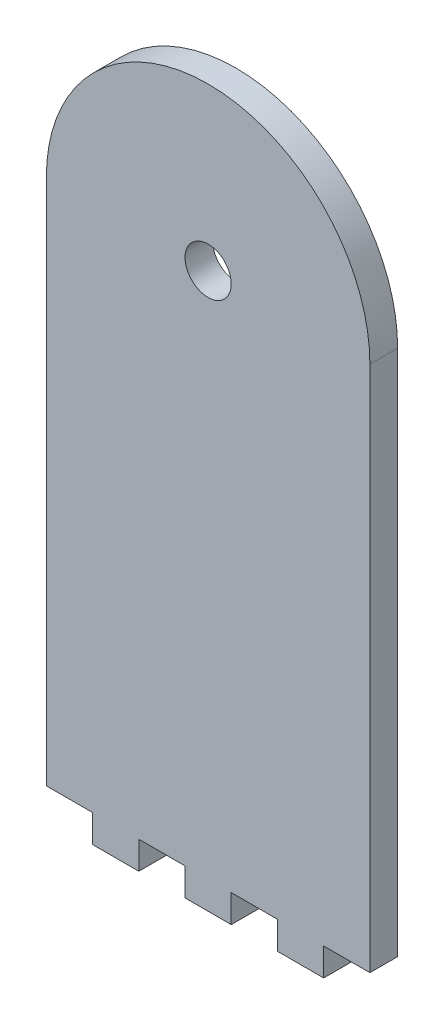
SolidWorks part; units mm, degrees
ref_plane "Alzado" through (0, 0, 0) normal (0, 0, 1) x (1, 0, 0)
ref_plane "Planta" through (0, 0, 0) normal (0, 1, 0) x (1, 0, 0)
ref_plane "Vista lateral" through (0, 0, 0) normal (1, 0, 0) x (0, 0, -1)
sketch "Croquis1" plane through (0, 0, 0) normal (0, 0, 1) x (1, 0, 0)
  line L0 (-17.5, 30) -> (17.5, 30) construction
  line L1 (-12.5, -30) -> (-7.5, -30)
  line L2 (-17.5, -27) -> (-17.5, 30)
  line L4 (17.5, -27) -> (17.5, 30)
  line L5 (-17.5, -30) -> (17.5, 30) construction
  line L6 (-17.5, 30) -> (17.5, -30) construction
  line L22 (-12.5, -30) -> (-12.5, -27)
  line L23 (-17.5, -27) -> (17.5, -27) construction
  line L24 (-17.5, -27) -> (-12.5, -27)
  line L26 (-7.5, -30) -> (-7.5, -27)
  line L27 (-7.5, -27) -> (-2.5, -27)
  line L28 (-2.5, -27) -> (-2.5, -30)
  line L29 (-2.5, -30) -> (2.5, -30)
  line L30 (2.5, -30) -> (2.5, -27)
  line L31 (2.5, -27) -> (7.5, -27)
  line L32 (7.5, -27) -> (7.5, -30)
  line L33 (7.5, -30) -> (12.5, -30)
  line L34 (12.5, -30) -> (12.5, -27)
  line L35 (12.5, -27) -> (17.5, -27)
  line L38 (-17.5, -27) -> (-17.5, -30) construction
  line L39 (-17.5, -30) -> (17.5, -30) construction
  line L40 (17.5, -30) -> (17.5, -27) construction
  arc A0 (-17.5, 30) -> (17.5, 30) centre (0, 30) cw
  circle A1 centre (0, 30) radius 2.5
  point P0 (0, 0)
  point P30 (10, -30)
  point P36 (-2.5, -28.5)
  dimension "D2" = 5
  dimension "D1" = 35
  dimension "D7" = 60
  dimension "D8" = 3
  dimension "D9" = 5
  dimension "D10" = 5
  dimension "D11" = 5
  dimension "D12" = 5
  dimension "D13" = 5
extrude "Saliente-Extruir1" add sketch "Croquis1" along normal blind 3
